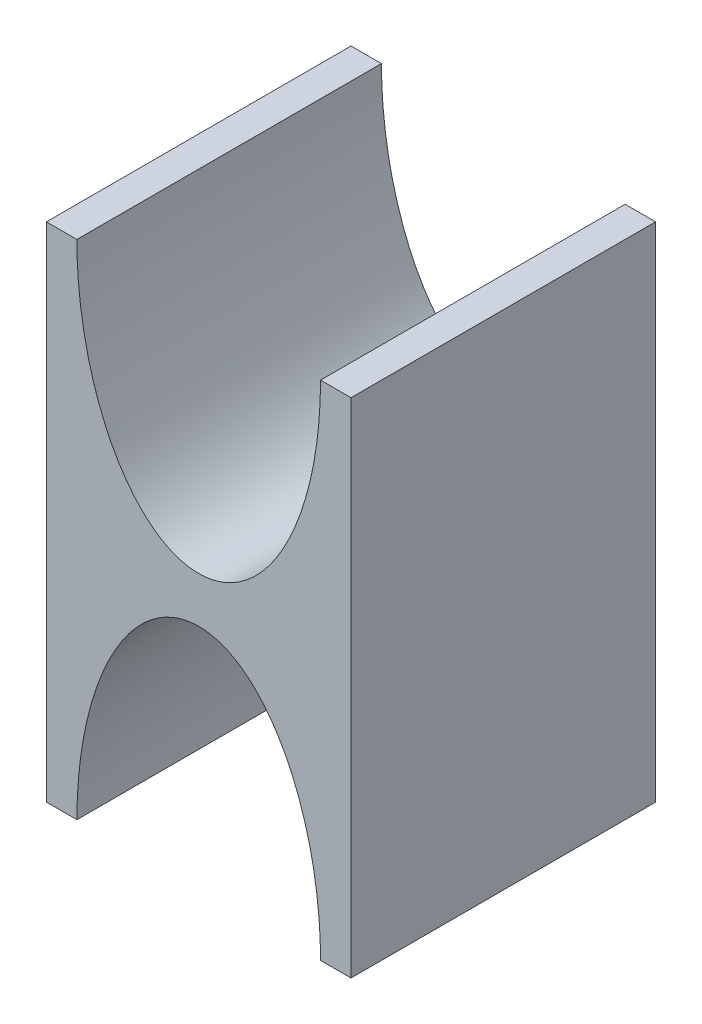
SolidWorks part; units mm, degrees
ref_plane "Front Plane" through (0, 0, 0) normal (0, 0, 1) x (1, 0, 0)
ref_plane "Top Plane" through (0, 0, 0) normal (0, 1, 0) x (1, 0, 0)
ref_plane "Right Plane" through (0, 0, 0) normal (1, 0, 0) x (0, 0, -1)
sketch "Sketch1" plane through (0, 0, 0) normal (0, 0, 1) x (1, 0, 0)
  line L0 (-8, 16.5) -> (-10, 16.5)
  line L1 (8, 16.5) -> (10, 16.5)
  line L2 (10, 16.5) -> (10, -16.5)
  line L3 (8, -16.5) -> (10, -16.5)
  line L4 (-10, 16.5) -> (-10, -16.5)
  line L7 (-8, -16.5) -> (-10, -16.5)
  ellipse E0 centre (0, -16.5) end of major axis (0, -1.5) minor radius 8 (-8, -16.5) -> (8, -16.5) cw
  ellipse E1 centre (0, 16.5) end of major axis (0, 1.5) minor radius 8 (8, 16.5) -> (-8, 16.5) cw
  point P0 (0, 0)
  point P8 (0, 0)
extrude "Boss-Extrude1" add sketch "Sketch1" along normal blind 20
